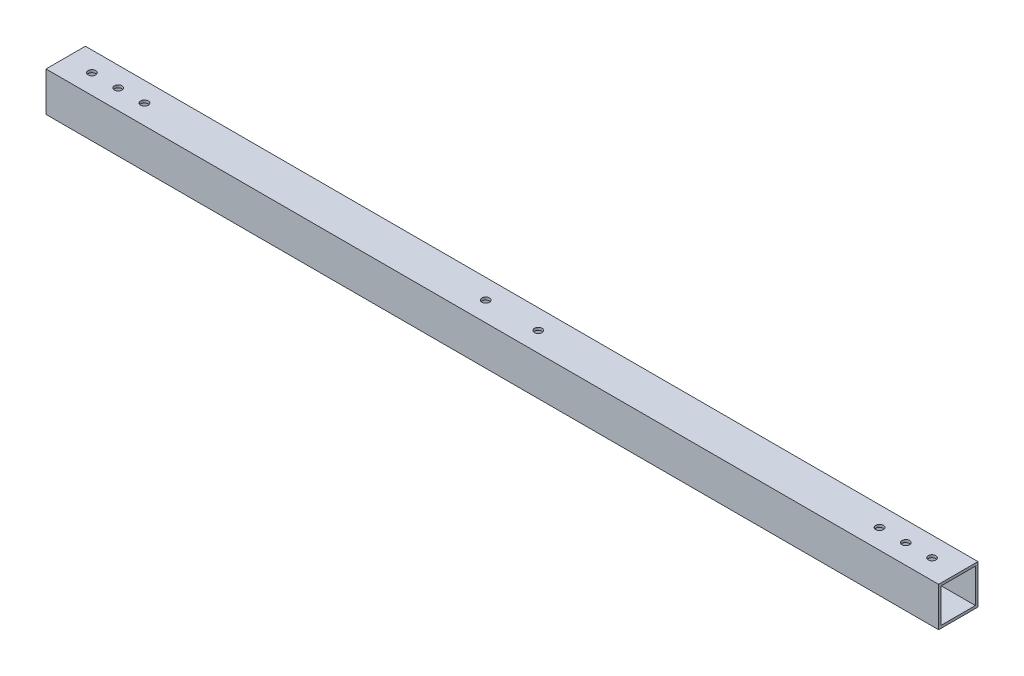
SolidWorks part; units mm, degrees
material "Thornel Mat VMA"
ref_plane "前视基准面" through (0, 0, 0) normal (0, 0, 1) x (1, 0, 0)
ref_plane "上视基准面" through (0, 0, 0) normal (0, 1, 0) x (1, 0, 0)
ref_plane "右视基准面" through (0, 0, 0) normal (1, 0, 0) x (0, 0, -1)
other "Configuration Table"
sketch "草图1" plane through (0, 0, 0) normal (1, 0, 0) x (0, 0, -1)
  line L1 (-6.5, 6.5) -> (6.5, 6.5)
  line L2 (-6.5, 6.5) -> (-6.5, -6.5)
  line L3 (-6.5, -6.5) -> (6.5, -6.5)
  line L4 (6.5, 6.5) -> (6.5, -6.5)
  line L5 (-6.5, 6.5) -> (6.5, -6.5) construction
  line L6 (-6.5, -6.5) -> (6.5, 6.5) construction
  line L7 (-7.5, 7.5) -> (7.5, 7.5)
  line L8 (-7.5, 7.5) -> (-7.5, -7.5)
  line L9 (-7.5, -7.5) -> (7.5, -7.5)
  line L10 (7.5, 7.5) -> (7.5, -7.5)
  line L11 (-7.5, 7.5) -> (7.5, -7.5) construction
  line L12 (-7.5, -7.5) -> (7.5, 7.5) construction
  point P0 (0, 0)
  point P6 (0, 0)
  dimension "D1" = 13
  dimension "D2" = 15
  dimension "D3" = 13
  dimension "D4" = 15
extrude "凸台-拉伸1" add sketch "草图1" along normal blind 340
sketch "草图2" plane through (0, -7.5, 0) normal (0, -1, 0) x (1, 0, 0)
  line L0 (0, 0) -> (340, 0) construction
  line L1 (340, 7.5) -> (340, -7.5) construction
  line L2 (170, 0) -> (170, -7.5) construction
  line L3 (340, -7.5) -> (0, -7.5) construction
  circle A0 centre (160, 0) radius 1.45
  circle A1 centre (180, 0) radius 1.45
  dimension "D1" = 2.9
  dimension "D2" = 10
extrude "切除-拉伸1" cut sketch "草图2" against normal through all
sketch "草图3" plane through (0, 7.5, 0) normal (0, 1, 0) x (1, 0, 0)
  line L0 (0, 7.5) -> (0, -7.5) construction
  line L2 (170, 7.5) -> (170, -7.5) construction
  line L3 (340, 7.5) -> (0, 7.5) construction
  line L4 (340, -7.5) -> (0, -7.5) construction
  circle A3 centre (180, 0) radius 1.45
  circle A4 centre (160, 0) radius 1.45
  circle A6 centre (20, 0) radius 1.45
  circle A7 centre (30, 0) radius 1.45
  circle A8 centre (10, 0) radius 1.45
  circle A11 centre (330, 0) radius 1.45
  circle A12 centre (310, 0) radius 1.45
  circle A13 centre (320, 0) radius 1.45
  dimension "D1" = 2.9
  dimension "D2" = 20
  dimension "D3" = 2.9
  dimension "D4" = 160
extrude "切除-拉伸2" cut sketch "草图3" against normal through all
